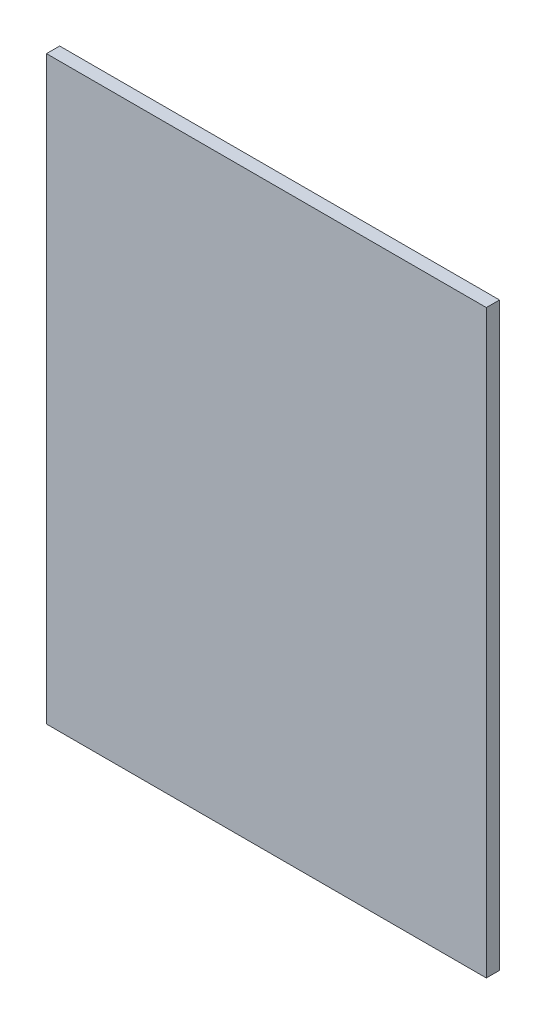
SolidWorks part; units mm, degrees
material "Teak"
ref_plane "Front Plane" through (0, 0, 0) normal (0, 0, 1) x (1, 0, 0)
ref_plane "Top Plane" through (0, 0, 0) normal (0, 1, 0) x (1, 0, 0)
ref_plane "Right Plane" through (0, 0, 0) normal (1, 0, 0) x (0, 0, -1)
sketch "Sketch1" plane through (0, 0, 0) normal (0, 0, 1) x (1, 0, 0)
  line L1 (0, 0) -> (600, 0)
  line L2 (0, 0) -> (0, 792)
  line L3 (0, 792) -> (600, 792)
  line L4 (600, 0) -> (600, 792)
  dimension "D1" = 600
  dimension "D2" = 792
extrude "Boss-Extrude1" add sketch "Sketch1" along normal blind 18
